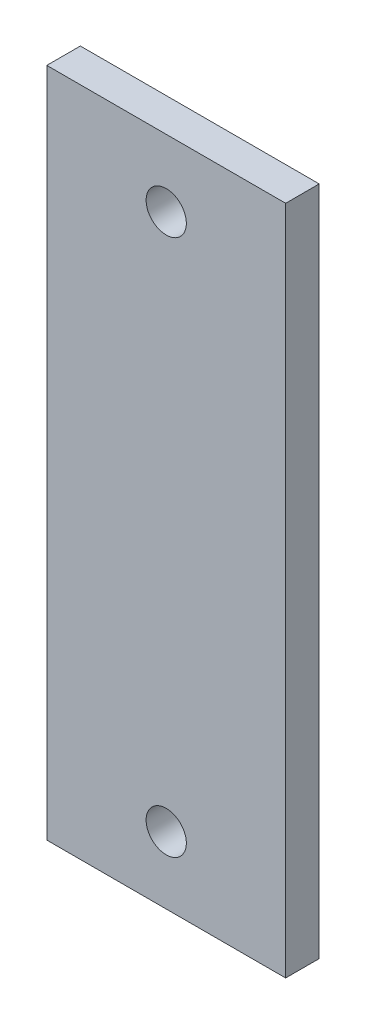
SolidWorks part; units mm, degrees
material "ABS"
ref_plane "前视基准面" through (0, 0, 0) normal (0, 0, 1) x (1, 0, 0)
ref_plane "上视基准面" through (0, 0, 0) normal (0, 1, 0) x (1, 0, 0)
ref_plane "右视基准面" through (0, 0, 0) normal (1, 0, 0) x (0, 0, -1)
sketch "草图1" plane through (0, 0, 0) normal (0, 0, 1) x (1, 0, 0)
  line L0 (0, -25) -> (0, 25) construction
  line L1 (-8.9, -25) -> (8.9, -25)
  line L2 (-8.9, -25) -> (-8.9, 25)
  line L3 (-8.9, 25) -> (8.9, 25)
  line L4 (8.9, -25) -> (8.9, 25)
  line L5 (-8.9, -25) -> (8.9, 25) construction
  line L6 (-8.9, 25) -> (8.9, -25) construction
  circle A0 centre (0, -20) radius 1.5
  circle A1 centre (0, 20) radius 1.5
  point P0 (0, 0)
  dimension "D3" = 3
  dimension "D5" = 5
  dimension "D1" = 17.8
  dimension "D2" = 50
  dimension "D4" = 5
extrude "凸台-拉伸1" add sketch "草图1" along normal blind 2.5
